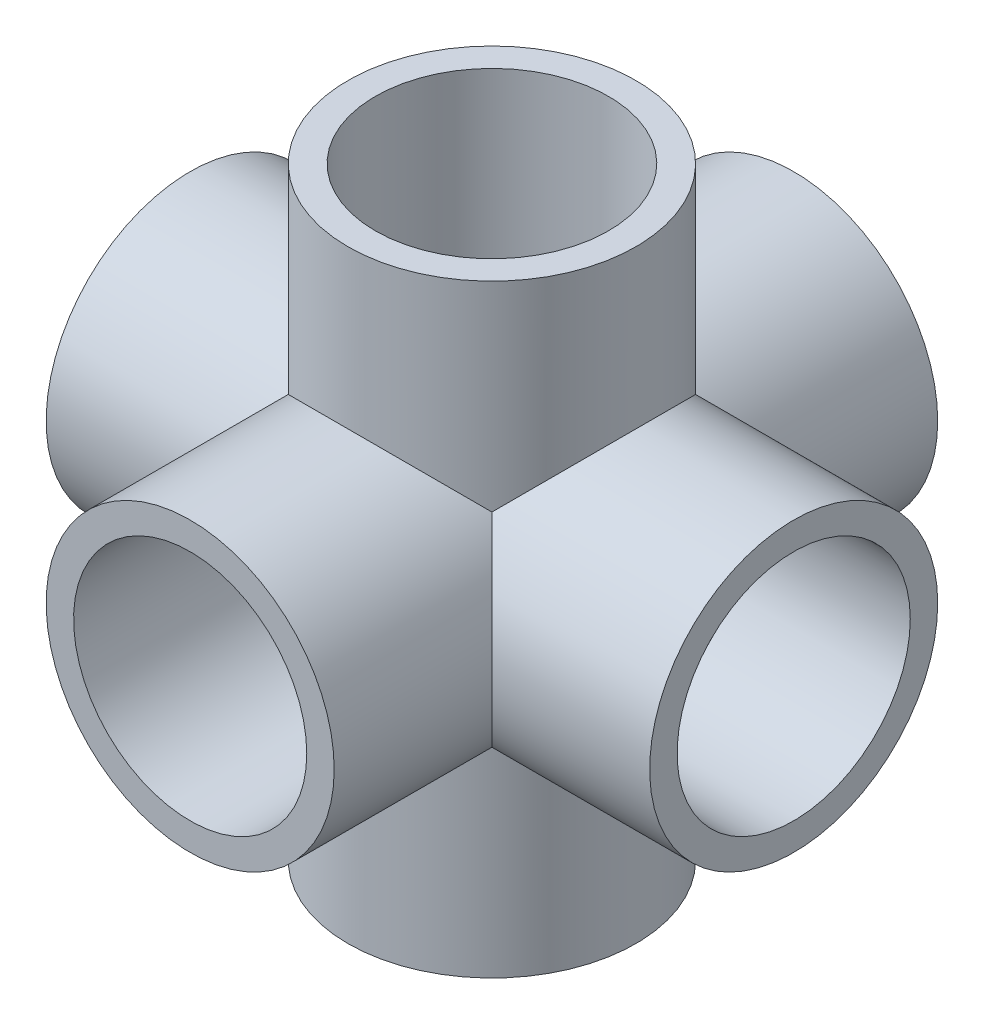
SolidWorks part; units mm, degrees
ref_plane "Front Plane" through (0, 0, 0) normal (0, 0, 1) x (1, 0, 0)
ref_plane "Top Plane" through (0, 0, 0) normal (0, 1, 0) x (1, 0, 0)
ref_plane "Right Plane" through (0, 0, 0) normal (1, 0, 0) x (0, 0, -1)
sketch "Sketch1" plane through (0, 0, 0) normal (0, 0, 1) x (1, 0, 0)
  circle A0 centre (0, 0) radius 16.6687
  dimension "D1" = 33.3375
extrude "Boss-Extrude1" add sketch "Sketch1" along normal blind 69.85 contours A0
sketch "Sketch3" plane through (0, 0, 69.85) normal (0, 0, 1) x (1, 0, 0)
  circle A0 centre (0, 0) radius 13.4938
  dimension "D1" = 26.9875
extrude "Cut-Extrude1" cut sketch "Sketch3" against normal blind 26.9875 and the other way through all
sketch "Sketch4" plane through (0, 0, 0) normal (1, 0, 0) x (0, 0, -1)
  line L0 (-69.85, 16.6687) -> (-69.85, -16.6687) construction
  circle A0 centre (-34.925, 0) radius 16.6687
  dimension "D1" = 33.3375
  dimension "D2" = 34.925
extrude "Boss-Extrude2" add sketch "Sketch4" along normal mid plane 69.85
sketch "Sketch5" plane through (34.925, 0, 0) normal (1, 0, 0) x (0, 0, -1)
  circle A0 centre (-34.925, 0) radius 12.7
  dimension "D1" = 25.4
extrude "Cut-Extrude2" cut sketch "Sketch5" against normal through all
sketch "Sketch11" plane through (0, 0, 0) normal (0, 0, 1) x (1, 0, 0)
  circle A0 centre (0, 0) radius 13.4938
  dimension "D1" = 26.9875
extrude "Cut-Extrude8" cut sketch "Sketch11" along normal blind 19.05
sketch "Sketch10" plane through (0, 0, 69.85) normal (0, 0, 1) x (1, 0, 0)
  circle A0 centre (0, 0) radius 12.7
  dimension "D1" = 25.4
extrude "Cut-Extrude5" cut sketch "Sketch10" against normal through all both and the other way through all
sketch "Sketch13" plane through (34.925, 0, 0) normal (1, 0, 0) x (0, 0, -1)
  circle A0 centre (-34.925, 0) radius 13.4937
  dimension "D1" = 26.9875
extrude "Cut-Extrude9" cut sketch "Sketch13" against normal blind 19.05
sketch "Sketch14" plane through (-34.925, 0, 0) normal (-1, 0, 0) x (0, 0, 1)
  circle A0 centre (34.925, 0) radius 13.4937
  dimension "D1" = 26.9875
extrude "Cut-Extrude10" cut sketch "Sketch14" against normal blind 19.05
sketch "Sketch15" plane through (0, 0, 0) normal (0, 1, 0) x (1, 0, 0)
  circle A0 centre (0, -34.925) radius 16.6687
  dimension "D1" = 33.3375
extrude "Boss-Extrude3" add sketch "Sketch15" along normal mid plane 69.85
sketch "Sketch16" plane through (0, 34.925, 0) normal (0, 1, 0) x (1, 0, 0)
  circle A0 centre (0, -34.925) radius 12.7
  dimension "D1" = 25.4
extrude "Cut-Extrude11" cut sketch "Sketch16" against normal through all
sketch "Sketch17" plane through (0, 34.925, 0) normal (0, 1, 0) x (1, 0, 0)
  circle A0 centre (0, -34.925) radius 13.4938
  dimension "D1" = 26.9875
extrude "Cut-Extrude12" cut sketch "Sketch17" against normal blind 19.05
sketch "Sketch18" plane through (0, -34.925, 0) normal (0, -1, 0) x (1, 0, 0)
  circle A0 centre (0, 34.925) radius 13.4938
  dimension "D1" = 26.9875
extrude "Cut-Extrude13" cut sketch "Sketch18" against normal blind 19.05
sketch "Sketch19" plane through (34.925, 0, 0) normal (1, 0, 0) x (0, 0, -1)
  circle A0 centre (-34.925, 0) radius 12.7
extrude "Cut-Extrude14" cut sketch "Sketch19" against normal through all
sketch "Sketch20" plane through (0, 0, 69.85) normal (0, 0, 1) x (1, 0, 0)
  circle A0 centre (0, 0) radius 12.7
extrude "Cut-Extrude15" cut sketch "Sketch20" against normal through all
